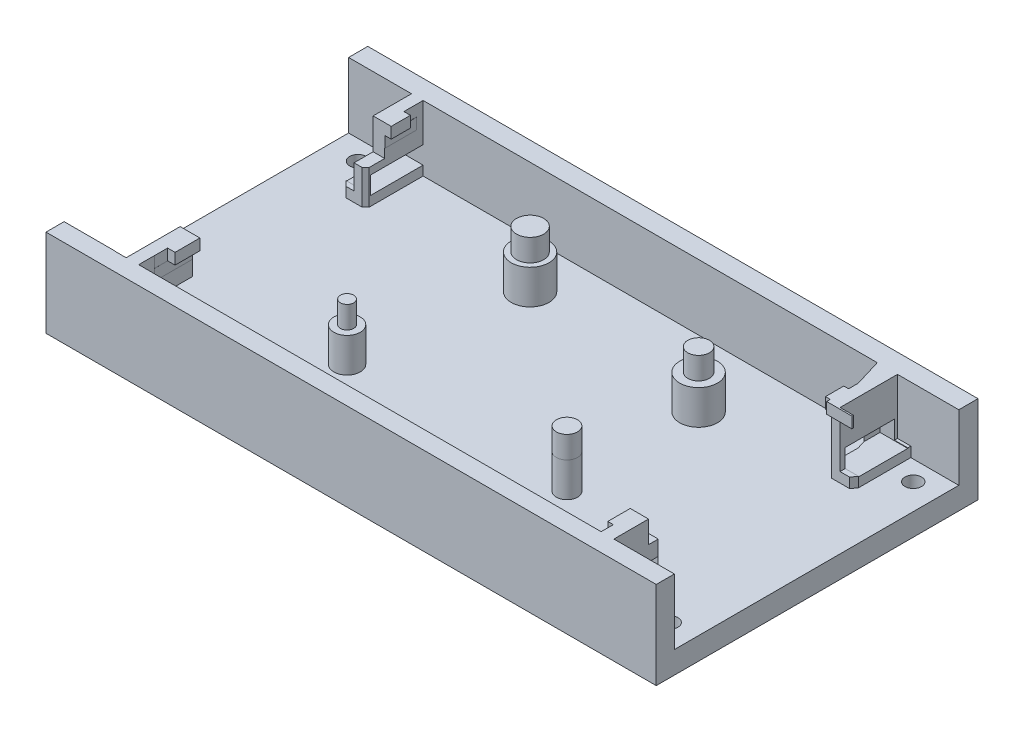
SolidWorks part; units mm, degrees
ref_plane "Front Plane" through (0, 0, 0) normal (0, 0, 1) x (1, 0, 0)
ref_plane "Top Plane" through (0, 0, 0) normal (0, 1, 0) x (1, 0, 0)
ref_plane "Right Plane" through (0, 0, 0) normal (1, 0, 0) x (0, 0, -1)
sketch "Sketch1" plane through (0, 0, 0) normal (0, 1, 0) x (1, 0, 0)
  line L1 (-55, 29) -> (55, 29)
  line L2 (-55, 29) -> (-55, -29)
  line L3 (-55, -29) -> (55, -29)
  line L4 (55, 29) -> (55, -29)
  line L5 (-55, 29) -> (55, -29) construction
  line L6 (-55, -29) -> (55, 29) construction
  point P0 (0, 0)
  dimension "D1" = 110
  dimension "D2" = 58
extrude "Boss-Extrude1" add sketch "Sketch1" along normal blind 4
sketch "Sketch2" plane through (0, 4, 0) normal (0, 1, 0) x (1, 0, 0)
  line L0 (644.9456, 681.943) -> (727.5716, 681.943) construction
  line L1 (-55, -29) -> (55, -29)
  line L2 (-55, -25.4327) -> (-55, -25.7327)
  line L3 (-55, 29) -> (-55, -29) construction
  line L4 (-46.1352, -19.0798) -> (-45.8379, -19.0798)
  line L5 (-41.263, -19.5058) -> (-41.5645, -19.5058)
  line L6 (-46.1352, 17.9805) -> (-45.9866, 17.9805)
  line L7 (-41.263, 18.1023) -> (-41.5645, 18.1023)
  line L8 (41.496, -17.7201) -> (41.7976, -17.7201)
  line L9 (46.494, -17.7492) -> (46.1918, -17.7492)
  line L10 (55, -29) -> (55, -25.7327)
  line L11 (55, -29) -> (55, 29) construction
  line L12 (55, -25.7327) -> (46.1918, -25.7327)
  line L13 (46.1918, -25.7327) -> (46.1918, -17.7492)
  line L14 (41.7976, -17.7201) -> (46.1918, -17.7492)
  line L15 (41.7976, -17.7201) -> (41.7976, -25.7327)
  line L16 (41.7976, -25.7327) -> (-41.5645, -25.7327)
  line L17 (-41.5645, -25.7327) -> (-41.5645, -19.5058)
  line L18 (-41.5645, -19.5058) -> (-41.5645, -16.0467)
  line L19 (-41.5645, -16.0467) -> (-45.8379, -16.0467)
  line L20 (-45.8379, -16.0467) -> (-45.8379, -19.0798)
  line L21 (-46.1352, -25.7327) -> (-55, -25.7327)
  line L22 (-55, -29) -> (-55, -25.7327)
  line L23 (-45.8379, -19.0798) -> (-45.8379, -25.7327)
  line L24 (-45.8379, -25.7327) -> (-46.1352, -25.7327)
  line L25 (-54.9943, 25.2433) -> (-54.9943, 25.5413)
  line L26 (-54.9943, 25.5413) -> (-54.9943, 29)
  line L27 (55, 29) -> (-55, 29) construction
  line L28 (-54.9943, 29) -> (55, 29)
  line L29 (55, 29) -> (55, 25.5413)
  line L30 (55, 25.5413) -> (46.3461, 25.5413)
  line L31 (46.3461, 25.5413) -> (46.3461, 16.1176)
  line L32 (46.3461, 16.1176) -> (45.6789, 15.1851)
  line L33 (45.6789, 15.1851) -> (42.4416, 15.1851)
  line L34 (42.4416, 15.1851) -> (41.7976, 16.1176)
  line L35 (41.7976, 16.1176) -> (41.7976, 20.6048)
  line L36 (41.7976, 20.6048) -> (40.3042, 25.5413)
  line L37 (40.3042, 25.5413) -> (-41.5645, 25.5413)
  line L38 (-41.5645, 25.5413) -> (-41.5645, 15.8229)
  line L39 (-41.5645, 15.8229) -> (-42.2023, 15.1851)
  line L40 (-42.2023, 15.1851) -> (-45.0883, 15.1851)
  line L41 (-45.0883, 15.1851) -> (-45.9866, 16.0834)
  line L42 (-45.9866, 16.0834) -> (-45.9866, 18.1023)
  line L43 (-45.9866, 18.1023) -> (-45.9866, 25.5413)
  line L44 (-45.9866, 25.5413) -> (-54.9943, 25.5413)
  circle A0 centre (-49.8597, -22.1014) radius 1.5961
  circle A1 centre (-49.8597, 21.8083) radius 1.6037
  circle A2 centre (50.2303, -22.1014) radius 1.6042
  circle A3 centre (50.2303, 21.8083) radius 1.5977
  circle A4 centre (-13.881, 17.1449) radius 3.399
  circle A5 centre (20.0803, 13.5549) radius 3.4078
  circle A6 centre (-19.025, -10.7045) radius 2.3844
  circle A7 centre (20.5897, -10.6834) radius 1.9027
  line M22 (55, -29) -> (55, 29)
  line M23 (55, 29) -> (-55, 29)
  line M24 (-55, 29) -> (-55, -29)
  line M25 (-55, -29) -> (55, -29)
  dimension "D1" = 82.626
  dimension "D2" = 0.3
extrude "Boss-Extrude2" add sketch "Sketch2" along normal blind 1.6 contours L44 L43 L42 L41 L40 L39 L38 L37 L36 L35 L34 L33 L32 L31 L30 L26 M22 M23 | A4 | A5 | A7 | A6 | L23 L24 L21 L12 L13 L14 L15 L16 L17 L18 L19 L20 M24 M25 M22
extrude "Boss-Extrude3" add sketch "Sketch2" along normal blind 6.2 contours L44 L43 L42 L41 L40 L39 L38 L37 L36 L35 L34 L33 L32 L31 L30 L26 M22 M23 | A4 | A5 | A7 | A6 | L23 L24 L21 L12 L13 L14 L15 L16 L17 L18 L19 L20 M24 M25 M22
sketch "Sketch4" plane through (0, 10.2, 0) normal (0, 1, 0) x (1, 0, 0)
  circle A0 centre (-13.881, 17.1449) radius 2.45
  circle A1 centre (20.0803, 13.5549) radius 1.95
  circle A2 centre (20.5897, -10.6834) radius 1.9
  circle A3 centre (-19.025, -10.7045) radius 1.2
  dimension "D1" = 4.9
  dimension "D2" = 3.9
  dimension "D3" = 3.8
  dimension "D4" = 2.4
extrude "Boss-Extrude4" add sketch "Sketch4" along normal blind 4 contours A0 | A3 | A1 | A2
sketch "Sketch5" plane through (0, 10.2, 0) normal (0, 1, 0) x (1, 0, 0)
  line L0 (-54.9943, 25.5413) -> (-54.9943, 29)
  line L1 (-54.9943, 29) -> (55, 29)
  line L2 (55, 29) -> (-54.9943, 29) construction
  line L3 (55, 25.5413) -> (55, 29) construction
  line L4 (55, 29) -> (55, 25.5413)
  line L5 (55, 25.5413) -> (46.3461, 25.5413)
  line L6 (46.3461, 25.5413) -> (46.3461, 16.1176) construction
  line L7 (55, 25.5413) -> (46.3461, 25.5413) construction
  line L8 (46.3461, 25.5413) -> (46.3461, 16.1176)
  line L9 (46.3461, 16.1176) -> (45.6789, 15.1851)
  line L10 (45.6789, 15.1851) -> (42.4416, 15.1851)
  line L11 (42.4416, 15.1851) -> (41.7976, 16.1176)
  line L12 (41.7976, 16.1176) -> (41.7976, 20.6048)
  line L13 (41.7976, 20.6048) -> (40.3042, 25.5413)
  line L14 (40.3042, 25.5413) -> (-41.5645, 25.5413)
  line L15 (-41.5645, 25.5413) -> (-41.5645, 18.6244)
  line L16 (-41.5645, 25.5413) -> (-41.5645, 15.8229) construction
  line L17 (-41.5645, 18.6244) -> (-45.9866, 18.6244)
  line L18 (-45.9866, 16.0834) -> (-45.9866, 25.5413) construction
  line L19 (-45.9866, 18.6244) -> (-45.9866, 25.5413)
  line L20 (-45.9866, 25.5413) -> (-54.9943, 25.5413)
  line L21 (-55, -29) -> (-55, -25.7327)
  line L22 (-55, -25.7327) -> (-45.8379, -25.7327)
  line L23 (-45.8379, -25.7327) -> (-45.8379, -16.0467)
  line L24 (-45.8379, -16.0467) -> (-41.5645, -16.0467)
  line L25 (-41.5645, -16.0467) -> (-41.5645, -25.7327)
  line L26 (-41.5645, -25.7327) -> (41.7976, -25.7327)
  line L27 (41.7976, -25.7327) -> (41.7976, -17.7201)
  line L28 (41.7976, -17.7201) -> (46.1918, -17.7492)
  line L29 (46.1918, -17.7492) -> (46.1918, -25.7327)
  line L30 (46.1918, -25.7327) -> (55, -25.7327)
  line L31 (55, -25.7327) -> (55, -29)
  line L32 (55, -29) -> (-55, -29)
extrude "Boss-Extrude5" add sketch "Sketch5" along normal blind 1.6 contours L20 L0 L1 L4 L5 L8 L9 L10 L11 L12 L13 L14 L15 L17 L19 | L32 L21 L22 L23 L24 L25 L26 L27 L28 L29 L30 L31
sketch "Sketch8" plane through (0, 11.8, 0) normal (0, 1, 0) x (1, 0, 0)
  line L0 (-45.9866, 25.5413) -> (-54.9943, 25.5413)
  line L1 (-54.9943, 25.5413) -> (-54.9943, 29)
  line L2 (-54.9943, 29) -> (55, 29)
  line L3 (55, 29) -> (55, 25.5413)
  line L4 (55, 25.5413) -> (46.3461, 25.5413)
  line L5 (46.3461, 25.5413) -> (46.3461, 16.1176)
  line L6 (46.3461, 16.1176) -> (45.6789, 15.1851)
  line L7 (45.6789, 15.1851) -> (42.4416, 15.1851)
  line L8 (42.4416, 15.1851) -> (41.7976, 16.1176)
  line L9 (41.7976, 16.1176) -> (41.8045, 16.1176)
  line L10 (41.8045, 20.6055) -> (41.8045, 16.1176)
  line L11 (41.8045, 20.6055) -> (41.7976, 20.6048)
  line L12 (41.7976, 20.6048) -> (40.3042, 25.5413)
  line L13 (40.3042, 25.5413) -> (-41.5645, 25.5413)
  line L14 (-41.5645, 25.5413) -> (-41.5645, 24.347)
  line L15 (-41.5645, 25.5413) -> (-41.5645, 18.6244) construction
  line L16 (-41.5645, 24.347) -> (-41.5424, 24.347)
  line L17 (-41.5424, 24.347) -> (-41.5424, 18.6244)
  line L18 (-41.5424, 18.6244) -> (-45.9866, 18.6244)
  line L19 (-45.9866, 18.6244) -> (-45.9866, 25.5413)
  line L20 (-55, -29) -> (-55, -25.7327)
  line L21 (-55, -25.7327) -> (-45.8379, -25.7327)
  line L22 (-45.8379, -25.7327) -> (-45.8379, -16.0467)
  line L23 (-45.8379, -16.0467) -> (-41.5645, -16.0467)
  line L24 (-41.5645, -16.0467) -> (-41.5532, -16.0467)
  line L25 (-41.5532, -16.0467) -> (-41.5532, -22.9192)
  line L26 (-41.5532, -22.9192) -> (-41.5645, -22.9192)
  line L27 (-41.5645, -25.7327) -> (-41.5645, -16.0467) construction
  line L28 (-41.5645, -22.9192) -> (-41.5645, -25.7327)
  line L29 (-41.5645, -25.7327) -> (41.7976, -25.7327)
  line L30 (41.7976, -25.7327) -> (41.7976, -23.239)
  line L31 (41.7976, -17.7201) -> (41.7976, -25.7327) construction
  line L32 (41.7976, -23.239) -> (41.7835, -23.239)
  line L33 (41.7835, -23.239) -> (41.7835, -19.4829)
  line L34 (41.7835, -19.4829) -> (46.1918, -19.4829)
  line L35 (46.1918, -17.7492) -> (46.1918, -25.7327) construction
  line L36 (46.1918, -19.4829) -> (46.1918, -25.7327)
  line L37 (46.1918, -25.7327) -> (55, -25.7327)
  line L38 (55, -25.7327) -> (55, -29)
  line L39 (55, -29) -> (-55, -29)
extrude "Boss-Extrude7" add sketch "Sketch8" along normal blind 2 contours L19 L0 L1 L2 L3 L4 L5 L6 L7 L8 L9 L10 L11 L12 L13 L14 L16 L17 L18 | L39 L20 L21 L22 L23 L24 L25 L26 L28 L29 L30 L32 L33 L34 L36 L37 L38
sketch "Sketch10" plane through (-45.8379, 0, 0) normal (-1, 0, 0) x (0, 0, 1)
  line L0 (16.0467, 13.8) -> (16.0467, 4) construction
  line L1 (16.0467, 5.7055) -> (25.7327, 5.7055)
  line L2 (16.0467, 5.7055) -> (16.0467, 9.0951)
  line L3 (16.0467, 9.0951) -> (25.7327, 9.0951)
  line L4 (25.7327, 5.7055) -> (25.7327, 9.0951)
  line L5 (25.7327, 13.8) -> (25.7327, 4) construction
extrude "Cut-Extrude1" cut sketch "Sketch10" against normal blind 5
sketch "Sketch11" plane through (-45.9866, 0, 0) normal (-1, 0, 0) x (0, 0, 1)
  line L0 (-16.0834, 10.2) -> (-16.0834, 4) construction
  line L1 (-16.0834, 5.7055) -> (-25.5413, 5.7055)
  line L2 (-16.0834, 5.7055) -> (-16.0834, 8.9)
  line L3 (-16.0834, 8.9) -> (-25.5413, 8.9)
  line L4 (-25.5413, 5.7055) -> (-25.5413, 8.9)
  line L5 (-25.5413, 13.8) -> (-25.5413, 4) construction
extrude "Cut-Extrude2" cut sketch "Sketch11" against normal blind 5
sketch "Sketch12" plane through (46.1918, 0, 0) normal (1, 0, 0) x (0, 0, -1)
  line L0 (-17.7492, 11.8) -> (-17.7492, 4) construction
  line L1 (-17.7492, 5.7055) -> (-25.3209, 5.7055)
  line L2 (-17.7492, 5.7055) -> (-17.7492, 9.0951)
  line L3 (-17.7492, 9.0951) -> (-25.3209, 9.0951)
  line L4 (-25.3209, 5.7055) -> (-25.3209, 9.0951)
  line L5 (-16.0467, 5.7055) -> (-25.7327, 5.7055) construction
  line L6 (-25.7327, 9.0951) -> (-16.0467, 9.0951) construction
extrude "Cut-Extrude3" cut sketch "Sketch12" against normal blind 5
sketch "Sketch13" plane through (46.3461, 0, 0) normal (1, 0, 0) x (0, 0, -1)
  line L0 (16.1176, 13.8) -> (16.1176, 4) construction
  line L1 (16.1176, 5.7055) -> (24.9952, 5.7055)
  line L2 (16.1176, 5.7055) -> (16.1176, 9.0951)
  line L3 (16.1176, 9.0951) -> (24.9952, 9.0951)
  line L4 (24.9952, 5.7055) -> (24.9952, 9.0951)
extrude "Cut-Extrude4" cut sketch "Sketch13" against normal blind 5
sketch "Sketch14" plane through (0, 13.8, 0) normal (0, 1, 0) x (1, 0, 0)
  line L0 (-55, -29) -> (-55, -25.7327)
  line L1 (-55, -25.7327) -> (-45.8379, -25.7327)
  line L2 (-45.8379, -25.7327) -> (-45.8379, -16.0467)
  line L3 (-45.8379, -16.0467) -> (-41.5645, -16.0467)
  line L4 (-41.5645, -16.0467) -> (-45.8379, -16.0467) construction
  line L5 (-45.8379, -16.0467) -> (-41.5532, -16.0467) construction
  line L6 (-41.5645, -16.0467) -> (-40.2121, -16.0467)
  line L7 (-40.2121, -16.0467) -> (-40.2121, -20.5243)
  line L8 (-40.2121, -20.5243) -> (-41.5532, -20.5243)
  line L9 (-41.5532, -16.0467) -> (-41.5532, -22.9192) construction
  line L10 (-41.5532, -20.5243) -> (-41.5645, -25.7327)
  line L11 (-41.5645, -25.7327) -> (41.7976, -25.7327)
  line L12 (41.7976, -25.7327) -> (41.7976, -23.5311)
  line L13 (41.7976, -17.7201) -> (41.7976, -25.7327) construction
  line L14 (41.7976, -23.5311) -> (40.7966, -23.5311)
  line L15 (40.7966, -23.5311) -> (40.7966, -19.4829)
  line L16 (40.7966, -19.4829) -> (46.1918, -19.4829)
  line L17 (46.1918, -19.4829) -> (46.1918, -25.7327)
  line L18 (46.1918, -25.7327) -> (55, -25.7327)
  line L19 (55, -25.7327) -> (55, -29)
  line L20 (55, -29) -> (-55, -29)
  line L21 (-54.9943, 29) -> (55, 29)
  line L22 (55, 29) -> (55, 25.5413)
  line L23 (55, 25.5413) -> (46.3461, 25.5413)
  line L24 (46.3461, 25.5413) -> (46.3461, 16.1176)
  line L29 (41.7976, 20.6048) -> (40.3042, 25.5413)
  line L30 (40.3042, 25.5413) -> (-41.5645, 25.5413)
  line L31 (-41.5645, 25.5413) -> (-41.5645, 22.0749)
  line L32 (-41.5645, 25.5413) -> (-41.5645, 15.8229) construction
  line L33 (-41.5645, 22.0749) -> (-40.394, 22.0749)
  line L34 (-40.394, 22.0749) -> (-40.394, 18.6244)
  line L35 (-40.394, 18.6244) -> (-45.9866, 18.6244)
  line L36 (-45.9866, 18.6244) -> (-45.9866, 25.5413)
  line L37 (-45.9866, 25.5413) -> (-54.9943, 25.5413)
  line L38 (-54.9943, 25.5413) -> (-54.9943, 29)
  line L39 (41.7976, 19.1643) -> (41.7976, 16.1176)
  line L44 (41.7976, 14.9169) -> (46.3461, 14.9169)
  line L45 (46.3461, 14.9169) -> (46.3461, 16.1176)
  line L46 (41.7976, 15.5775) -> (40.9315, 15.5775)
  line L47 (40.9315, 15.5775) -> (40.9315, 18.8804)
  line L48 (40.9315, 18.8804) -> (41.7976, 18.8804)
  line L49 (41.7976, 16.1176) -> (41.7976, 18.8804)
  line L50 (41.7976, 15.5775) -> (41.7976, 14.9169)
  line L51 (41.7976, 20.6048) -> (41.7976, 18.8804)
extrude "Boss-Extrude11" add sketch "Sketch14" along normal blind 2
sketch "Sketch15" plane through (0, 15.8, 0) normal (0, 1, 0) x (1, 0, 0)
  line L0 (-42.2023, 15.1851) -> (-45.0883, 15.1851) construction
  line L1 (-45.9866, 25.5413) -> (-43.6581, 25.5413)
  line L2 (-45.9866, 25.5413) -> (-45.9866, 15.1851)
  line L3 (-45.9866, 15.1851) -> (-43.6581, 15.1851)
  line L4 (-43.6581, 25.5413) -> (-43.6581, 15.1851)
  line L5 (-45.8379, -16.0467) -> (-45.8379, -25.7327) construction
  line L6 (-45.8379, -16.0467) -> (-43.7754, -16.0467)
  line L7 (-45.8379, -16.0467) -> (-45.8379, -25.7732)
  line L8 (-45.8379, -25.7732) -> (-43.7754, -25.7732)
  line L9 (-43.7754, -16.0467) -> (-43.7754, -25.7732)
  line L10 (-40.2121, -16.0467) -> (-45.8379, -16.0467) construction
  line L11 (41.7976, -17.7201) -> (46.1918, -17.7492) construction
  line L12 (46.1918, -25.7327) -> (44.0971, -25.7327)
  line L13 (46.1918, -25.7327) -> (46.1918, -17.7353)
  line L14 (46.1918, -17.7353) -> (44.0971, -17.7353)
  line L15 (44.0971, -25.7327) -> (44.0971, -17.7353)
  line L16 (45.6789, 15.1851) -> (42.4416, 15.1851) construction
  line L17 (46.3461, 25.5413) -> (43.9476, 25.5413)
  line L18 (46.3461, 25.5413) -> (46.3461, 15.1851)
  line L19 (46.3461, 15.1851) -> (43.9476, 15.1851)
  line L20 (43.9476, 25.5413) -> (43.9476, 15.1851)
extrude "Cut-Extrude5" cut sketch "Sketch15" against normal blind 10 contours L7 L6 L9 L8 | L2 L1 L4 L3 | L18 L17 L20 L19 | L13 L12 L15 L14
sketch "Sketch16" plane through (0, 4, 0) normal (0, 1, 0) x (1, 0, 0)
  circle A0 centre (-49.7505, -21.9174) radius 1.5
  circle A1 centre (-49.7505, 21.9922) radius 1.5
  circle A2 centre (50.3395, -21.9174) radius 1.5
  circle A3 centre (50.3395, 21.9922) radius 1.5
  dimension "D1" = 3
  dimension "D2" = 3
  dimension "D3" = 3
  dimension "D4" = 3
extrude "Cut-Extrude9" cut sketch "Sketch16" against normal blind 5 contours A1 | A0 | A2 | A3
